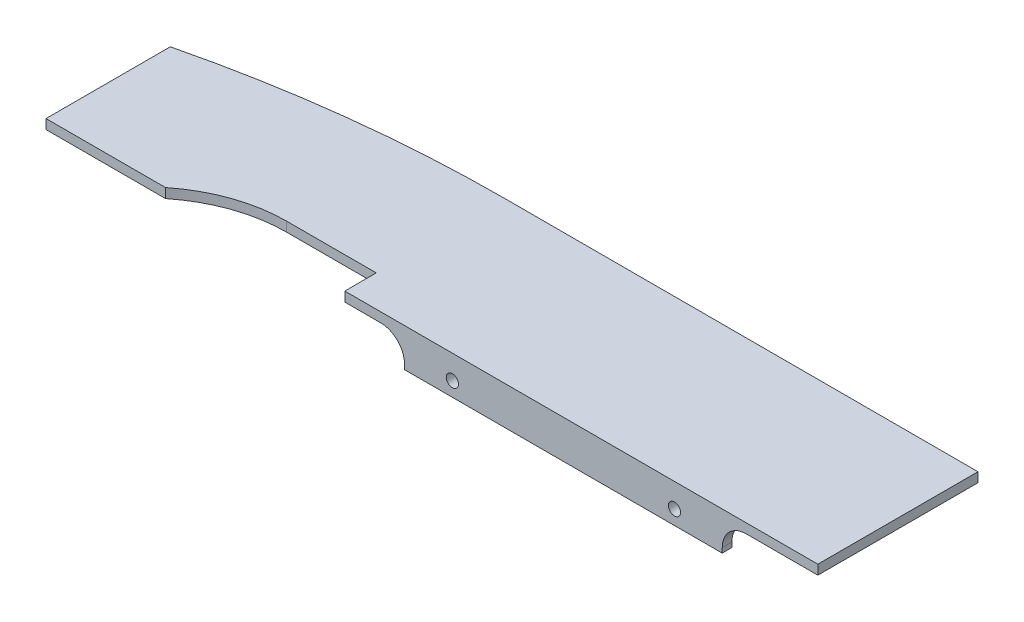
SolidWorks part; units mm, degrees
ref_plane "Front Plane" through (0, 0, 0) normal (0, 0, 1) x (1, 0, 0)
ref_plane "Top Plane" through (0, 0, 0) normal (0, 1, 0) x (1, 0, 0)
ref_plane "Right Plane" through (0, 0, 0) normal (1, 0, 0) x (0, 0, -1)
sketch "Sketch1" plane through (0, 0, 0) normal (0, 0, 1) x (1, 0, 0)
  line L1 (-182.9174, 55.8) -> (-50, 55.8)
  line L2 (-182.9174, 55.8) -> (-182.9174, 43.8)
  line L3 (-182.9174, 43.8) -> (-50, 43.8)
  line L4 (-50, 55.8) -> (-50, 43.8)
  line L5 (-182.9174, 0) -> (-182.9174, 55.8) construction
  line L6 (-50, -0.2) -> (-50, 55.8) construction
  line L7 (-182.9174, 27.9) -> (-50, 27.8) construction
  line L8 (-116.4587, 27.85) -> (-116.4587, 55.8) construction
  line L9 (-207.9174, 59.8) -> (-10, 59.8) construction
  circle A0 centre (-162.9174, 49.8) radius 2.55
  circle A1 centre (-70, 49.8) radius 2.55
  point P20 (-182.9174, 49.8)
  dimension "D2" = 20
  dimension "D4" = 5.1
  dimension "D5" = 5.1
  dimension "D1" = 12
  dimension "D3" = 20
  dimension "D6" = 4
extrude "Boss-Extrude1" add sketch "Sketch1" along normal blind 4
sketch "Sketch2" plane through (0, 55.8, 0) normal (0, 1, 0) x (1, 0, 0)
  line L1 (-332.9174, -67) -> (25, -67) construction
  line L2 (-207.9174, 0) -> (-10, 0)
  line L3 (-207.9174, 0) -> (-207.9174, -67)
  line L4 (-207.9174, -67) -> (-10, -67)
  line L5 (-10, 0) -> (-10, -67)
  line L6 (-10, 0) -> (-10, 4) construction
extrude "Boss-Extrude2" add sketch "Sketch2" along normal blind 4
sketch "Sketch3" plane through (0, 0, 67) normal (0, 0, -1) x (-1, 0, 0)
  line L4 (182.9174, 43.8) -> (182.9174, 55.8)
  line L5 (50, 43.8) -> (182.9174, 43.8)
  line L6 (50, 55.8) -> (50, 43.8)
  line L7 (182.9174, 55.8) -> (50, 55.8)
  line L8 (182.9174, 43.8) -> (182.9174, 55.8)
  line L9 (50, 43.8) -> (182.9174, 43.8)
  line L10 (50, 55.8) -> (50, 43.8)
  line L11 (182.9174, 55.8) -> (50, 55.8)
  circle A0 centre (162.9174, 49.8) radius 2.55 construction
  circle A1 centre (70, 49.8) radius 2.55 construction
  circle A2 centre (162.9174, 49.8) radius 2.55
  circle A3 centre (70, 49.8) radius 2.55
  dimension "D1" = 0
extrude "Boss-Extrude3" add sketch "Sketch3" along normal blind 4
fillet "Fillet1" radius 10 4 edges at (-182.9174, 55.8, 2) (-182.9174, 55.8, 65) (-50, 55.8, 2) (-50, 55.8, 65)
fillet "Fillet2" radius 2.5 2 edges at (-116.4587, 55.8, 63) (-116.4587, 55.8, 4)
sketch "Sketch4" plane through (0, 59.8, 0) normal (0, 1, 0) x (1, 0, 0)
  line L0 (-266.5674, -63) -> (-224.2674, -63) construction
  line L1 (-207.9174, 0) -> (-332.9174, 0)
  line L2 (-207.9174, 0) -> (-207.9174, -67)
  line L3 (-207.9174, -67) -> (-332.9174, -67)
  line L4 (-332.9174, 0) -> (-332.9174, -67)
  line L5 (-332.9174, -67) -> (25, -67) construction
  line L6 (-245.4174, -53.8375) -> (-207.9174, -53.8375)
  arc A0 (-282.9174, -67) -> (-207.9174, -67) centre (-245.4174, -113.8375) cw
  arc A1 (-332.9174, -15) -> (-207.9174, 0) centre (-207.9174, -528.3333) cw
  point P11 (-245.4174, -63)
  point P12 (-245.4174, -53.8375)
  line M5 (-207.9174, 0) -> (-207.9174, -67)
  dimension "D1" = 60
  dimension "D2" = 15
extrude "Boss-Extrude4" add sketch "Sketch4" against normal up to surface (4 mm away) contours A1 L4 L3 A0 L6 M5 up to face at (-113.9587, 55.8, 33.5)
